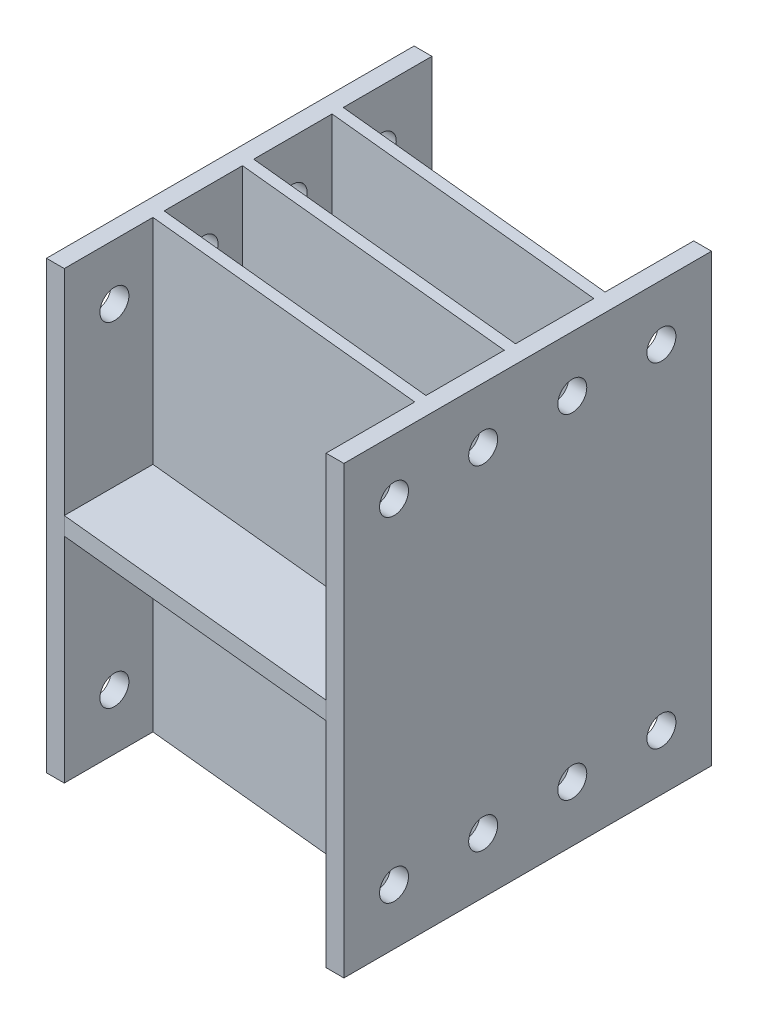
SolidWorks part; units mm, degrees
ref_plane "前视基准面" through (0, 0, 0) normal (0, 0, 1) x (1, 0, 0)
ref_plane "上视基准面" through (0, 0, 0) normal (0, 1, 0) x (1, 0, 0)
ref_plane "右视基准面" through (0, 0, 0) normal (1, 0, 0) x (0, 0, -1)
sketch "草图7" plane through (0, 0, 0) normal (1, 0, 0) x (0, -1, 0)
  line L1 (0, 0) -> (400, 0)
  line L2 (0, 0) -> (0, 330)
  line L3 (0, 330) -> (400, 330)
  line L4 (400, 0) -> (400, 330)
  dimension "D1" = 400
  dimension "D2" = 330
extrude "凸台-拉伸6" add sketch "草图7" along normal blind 16
sketch "草图8" plane through (16, 0, 0) normal (1, 0, 0) x (0, -1, 0)
  line L0 (0, 330) -> (0, 0) construction
  line L1 (0, 0) -> (400, 0) construction
  circle A0 centre (50, 45) radius 13
  dimension "D1" = 26
  dimension "D2" = 50
  dimension "D3" = 45
extrude "切除-拉伸2" cut sketch "草图8" against normal through all
pattern_linear "阵列(线性)1" count 2 spacing 300 along (0, -1, 0) count 4 spacing 80 along (0, 0, -1) of "切除-拉伸2"
sketch "草图9" plane through (16, 0, 0) normal (1, 0, 0) x (0, 0, -1)
  line L0 (-670, -200) -> (49330, -200) construction
  line L1 (330, -400) -> (330, 0) construction
  line L2 (0, 0) -> (0, -400) construction
  line L3 (-26, -192) -> (356, -192)
  line L4 (-26, -192) -> (-26, -208)
  line L7 (-26, -208) -> (356, -208)
  line L8 (356, -192) -> (356, -208)
  point P5 (330, -200)
  dimension "D1" = 8
  dimension "D2" = 8
  dimension "D3" = 26
  dimension "D4" = 26
extrude "凸台-拉伸7" add sketch "草图9" along normal blind 261
sketch "草图10" plane through (0, -208, 0) normal (0, -1, 0) x (-1, 0, 0)
  line L0 (-16, -26) -> (-16, 0)
  line L1 (-16, 0) -> (-277, -26)
  line L2 (-277, -26) -> (-16, -26)
  line L3 (-16, 330) -> (-277, 304)
  line L5 (-277, -26) -> (-277, 356) construction
  line L6 (-277, 304) -> (-277, 356)
  line L7 (-277, 356) -> (-16, 356)
  line L8 (-16, 356) -> (-16, 330)
extrude "切除-拉伸3" cut sketch "草图10" against normal through all
sketch "草图11" plane through (0, -208, 0) normal (0, -1, 0) x (1, 0, 0)
  line L0 (16, -79.5793) -> (277, -53.5793)
  line L1 (16, 0) -> (16, -330) construction
  line L2 (277, 26) -> (277, -304) construction
  line L3 (277, -53.5793) -> (277, -63.6288)
  line L4 (277, -63.6288) -> (16, -89.6288)
  line L5 (16, -89.6288) -> (16, -79.5793)
  line L6 (16, -170.0247) -> (277, -144.0247)
  line L7 (16, 0) -> (16, -330) construction
  line L8 (277, -144.0247) -> (277, -133.9753)
  line L9 (277, -133.9753) -> (16, -159.9753)
  line L10 (16, -159.9753) -> (16, -170.0247)
  line L11 (16, -240.3712) -> (277, -214.3712)
  line L12 (277, -214.3712) -> (277, -224.4207)
  line L13 (277, -224.4207) -> (16, -250.4207)
  line L14 (16, -250.4207) -> (16, -240.3712)
  line L15 (16, 0) -> (277, 26) construction
  line L16 (277, -139) -> (-49476.7433, -5095.3116) construction
  point P22 (277, -139)
  point P23 (16, -165)
  dimension "D1" = 10
  dimension "D2" = 10
  dimension "D3" = 10
  dimension "D4" = 80
  dimension "D5" = 80
extrude "凸台-拉伸8" add sketch "草图11" along normal blind 192
sketch "草图12" plane through (0, -192, 0) normal (0, 1, 0) x (1, 0, 0)
  line L0 (16, 79.5793) -> (16, 89.6288)
  line L1 (16, 89.6288) -> (277, 63.6288)
  line L2 (277, 63.6288) -> (277, 53.5793)
  line L3 (277, 53.5793) -> (16, 79.5793)
  line L4 (16, 159.9753) -> (16, 170.0247)
  line L5 (16, 170.0247) -> (277, 144.0247)
  line L6 (277, 144.0247) -> (277, 133.9753)
  line L7 (277, 133.9753) -> (16, 159.9753)
  line L8 (16, 240.3712) -> (16, 250.4207)
  line L9 (16, 250.4207) -> (277, 224.4207)
  line L10 (277, 224.4207) -> (277, 214.3712)
  line L11 (277, 214.3712) -> (16, 240.3712)
extrude "凸台-拉伸9" add sketch "草图12" along normal blind 192
sketch "草图13" plane through (277, 0, 0) normal (1, 0, 0) x (0, 0, -1)
  line L0 (-26, -192) -> (-26, -208) construction
  line L1 (-26, 0) -> (304, 0)
  line L2 (-26, 0) -> (-26, -400)
  line L3 (-26, -400) -> (304, -400)
  line L4 (304, 0) -> (304, -400)
  line L5 (304, -192) -> (304, -208) construction
  line L6 (240.3712, 0) -> (170.0247, 0) construction
  line L7 (170.0247, -400) -> (240.3712, -400) construction
extrude "凸台-拉伸10" add sketch "草图13" along normal blind 16
sketch "草图14" plane through (293, 0, 0) normal (1, 0, 0) x (0, 0, -1)
  line L0 (-26, -400) -> (304, -400) construction
  line L1 (-26, 0) -> (-26, -400) construction
  circle A0 centre (19, -350) radius 13
  dimension "D1" = 26
  dimension "D2" = 50
  dimension "D3" = 45
extrude "切除-拉伸4" cut sketch "草图14" against normal blind 16
pattern_linear "阵列(线性)2" count 4 spacing 80 along (0, 0, -1) count 2 spacing 300 along (0, 1, 0) of "切除-拉伸4"
